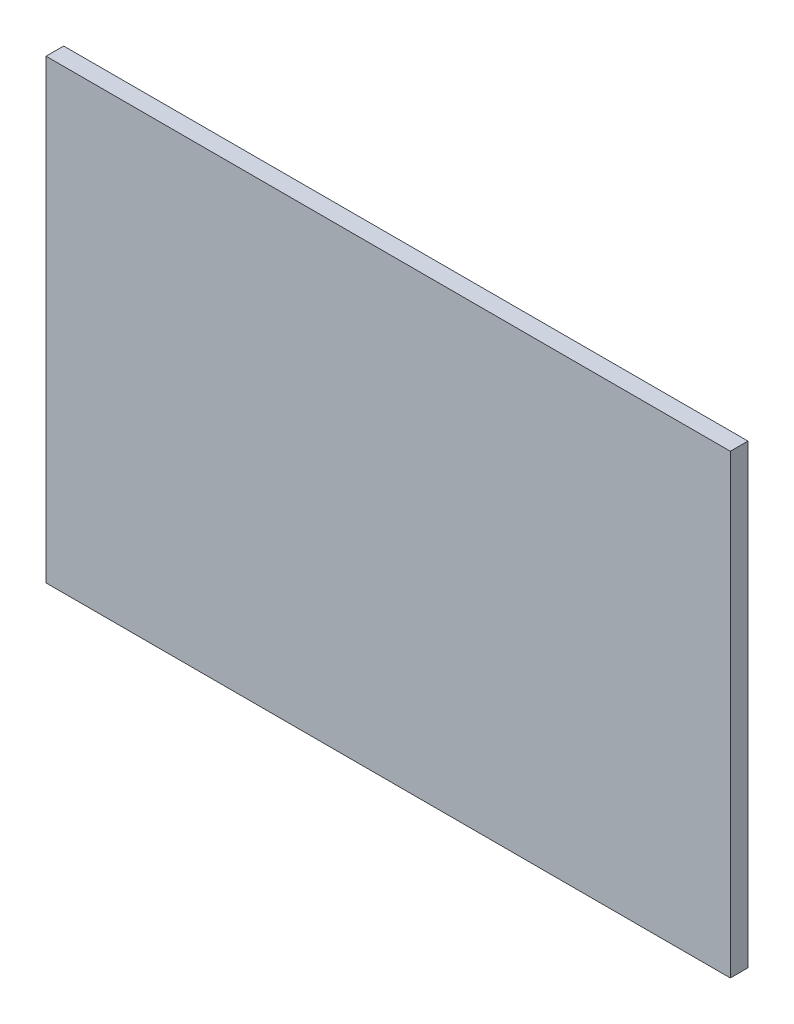
SolidWorks part; units mm, degrees
ref_plane "Front Plane" through (0, 0, 0) normal (0, 0, 1) x (1, 0, 0)
ref_plane "Top Plane" through (0, 0, 0) normal (0, 1, 0) x (1, 0, 0)
ref_plane "Right Plane" through (0, 0, 0) normal (1, 0, 0) x (0, 0, -1)
sketch "Sketch1" plane through (0, 0, 0) normal (0, 0, 1) x (1, 0, 0)
  line L1 (45, -30) -> (-45, -30)
  line L2 (45, -30) -> (45, 30)
  line L3 (45, 30) -> (-45, 30)
  line L4 (-45, -30) -> (-45, 30)
  line L5 (45, -30) -> (-45, 30) construction
  line L6 (45, 30) -> (-45, -30) construction
  point P0 (0, 0)
  dimension "D1" = 90
  dimension "D2" = 60
extrude "Boss-Extrude1" add sketch "Sketch1" along normal blind 2.32
